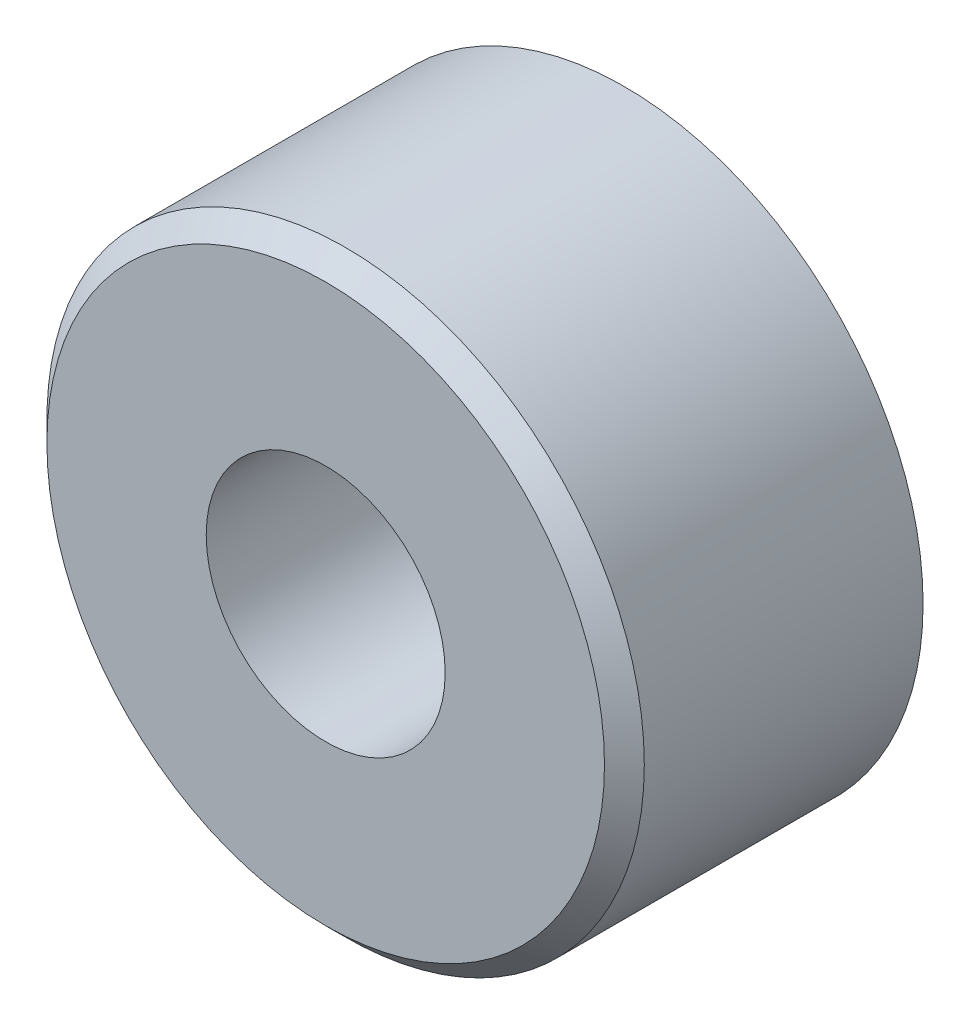
SolidWorks part; units mm, degrees
material "AISI 1020"
ref_plane "Front Plane" through (0, 0, 0) normal (0, 0, 1) x (1, 0, 0)
ref_plane "Top Plane" through (0, 0, 0) normal (0, 1, 0) x (1, 0, 0)
ref_plane "Right Plane" through (0, 0, 0) normal (1, 0, 0) x (0, 0, -1)
sketch "Sketch1" plane through (0, 0, 0) normal (0, 0, 1) x (1, 0, 0)
  circle A0 centre (0, 0) radius 7.5
  circle A1 centre (0, 0) radius 3
  dimension "D1" = 6
  dimension "D2" = 15
extrude "Boss-Extrude1" add sketch "Sketch1" along normal blind 7.5
chamfer "Chamfer1" distance 0.5 angle 45 1 edges at (7.5, 0, 7.5)
